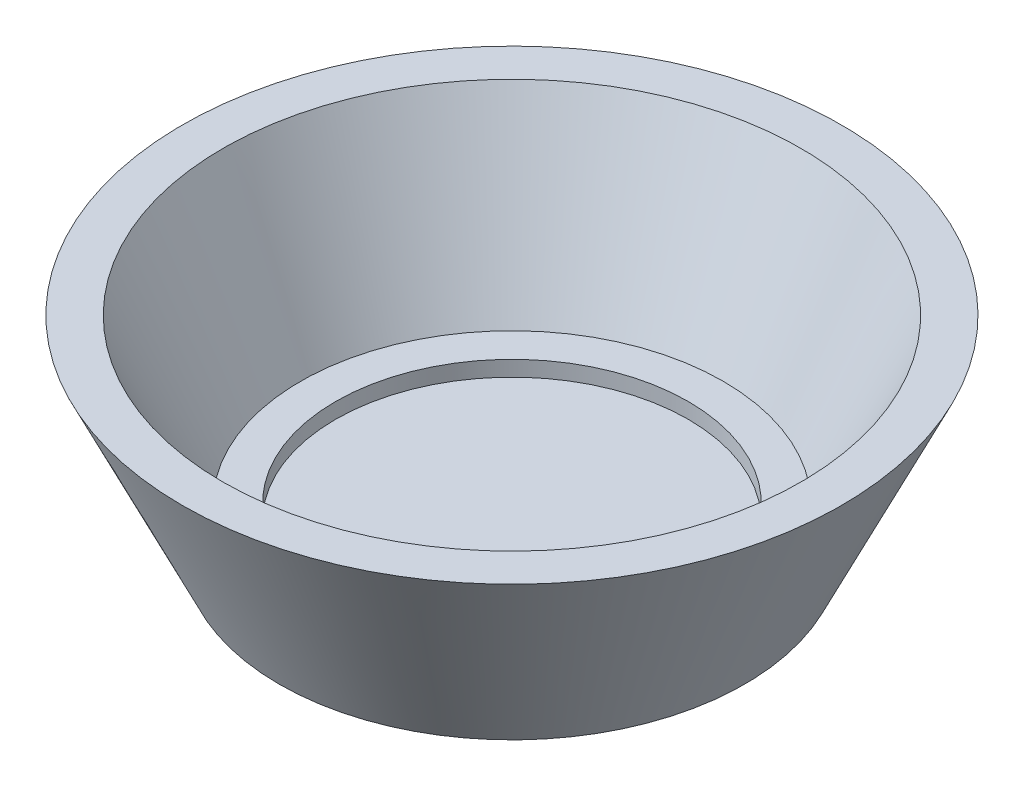
SolidWorks part; units mm, degrees
ref_plane "Front Plane" through (0, 0, 0) normal (0, 0, 1) x (1, 0, 0)
ref_plane "Top Plane" through (0, 0, 0) normal (0, 1, 0) x (1, 0, 0)
ref_plane "Right Plane" through (0, 0, 0) normal (1, 0, 0) x (0, 0, -1)
sketch "Sketch1" plane through (0, 0, 0) normal (0, 0, 1) x (1, 0, 0)
  line L0 (0, 73.2578) -> (0, -69.24) construction
  line L1 (0, 0) -> (75.2667, 0)
  line L2 (75.2667, 0) -> (106.6055, 65.7579)
  line L3 (106.6055, 65.7579) -> (93.4807, 65.7579)
  line L4 (93.4807, 65.7579) -> (68.3672, 13.0626)
  line L5 (68.3672, 13.0626) -> (0, 13.0626)
  line L6 (0, 13.0626) -> (0, 0)
revolve "Revolve1" add sketch "Sketch1" angle 360 about L0
sketch "Sketch2" plane through (0, 13.0626, 0) normal (0, 1, 0) x (1, 0, 0)
  circle A0 centre (0, 0) radius 57.0493
extrude "Cut-Extrude1" cut sketch "Sketch2" against normal blind 5
